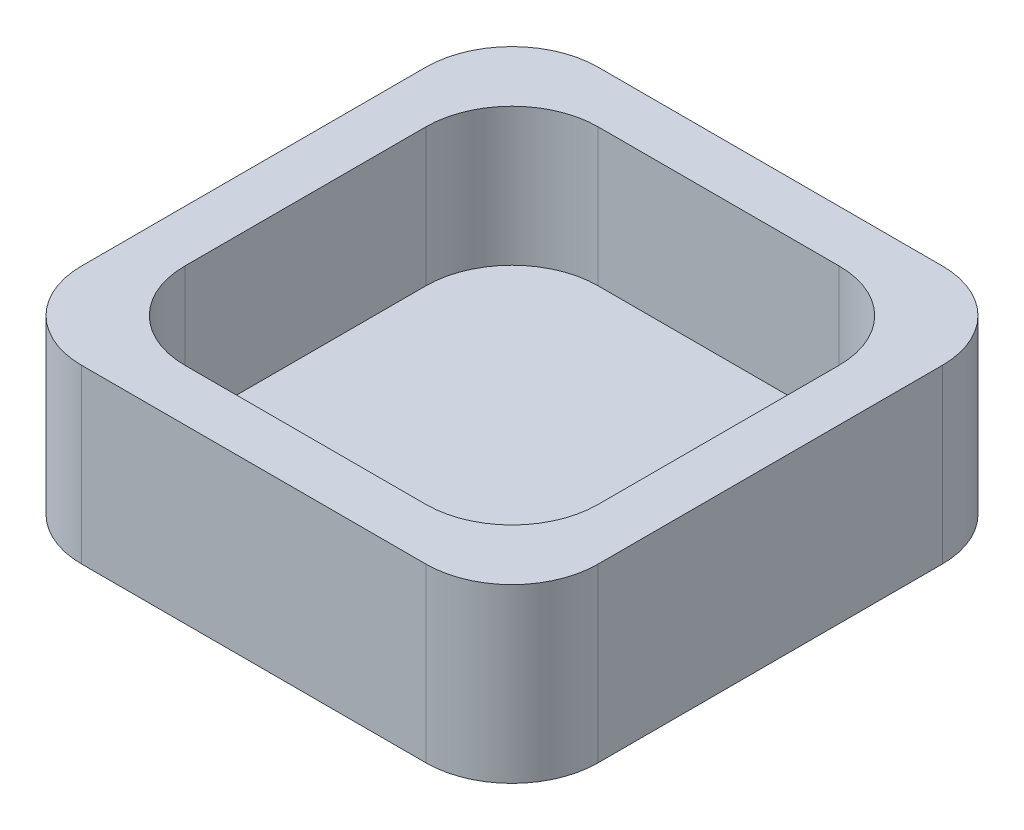
SolidWorks part; units mm, degrees
ref_plane "Front Plane" through (0, 0, 0) normal (0, 0, 1) x (1, 0, 0)
ref_plane "Top Plane" through (0, 0, 0) normal (0, 1, 0) x (1, 0, 0)
ref_plane "Right Plane" through (0, 0, 0) normal (1, 0, 0) x (0, 0, -1)
sketch "Sketch2" plane through (0, 0, 0) normal (0, 1, 0) x (1, 0, 0)
  line L1 (0, 0) -> (-30, 0)
  line L2 (0, 0) -> (0, -30)
  line L3 (0, -30) -> (-30, -30)
  line L4 (-30, 0) -> (-30, -30)
  dimension "D1" = 30
  dimension "D2" = 30
extrude "Boss-Extrude1" add sketch "Sketch2" along normal blind 10
sketch "Sketch4" plane through (0, 10, 0) normal (0, 1, 0) x (1, 0, 0)
  line L0 (0, 0) -> (-30, 0) construction
  line L1 (-27, -3) -> (-3, -3)
  line L2 (-27, -3) -> (-27, -27)
  line L3 (-27, -27) -> (-3, -27)
  line L4 (-3, -3) -> (-3, -27)
  line L5 (0, -30) -> (0, 0) construction
  line L6 (-30, 0) -> (-30, -30) construction
  line L7 (-30, -30) -> (0, -30) construction
  dimension "D1" = 3
  dimension "D2" = 3
  dimension "D3" = 3
  dimension "D4" = 3
extrude "Cut-Extrude1" cut sketch "Sketch4" against normal blind 8
fillet "Fillet1" radius 5 4 edges at (0, 5, 0) (0, 5, 30) (-30, 5, 30) (-30, 5, 0)
fillet "Fillet2" radius 5 4 edges at (-3, 6, 3) (-27, 6, 3) (-3, 6, 27) (-27, 6, 27)
